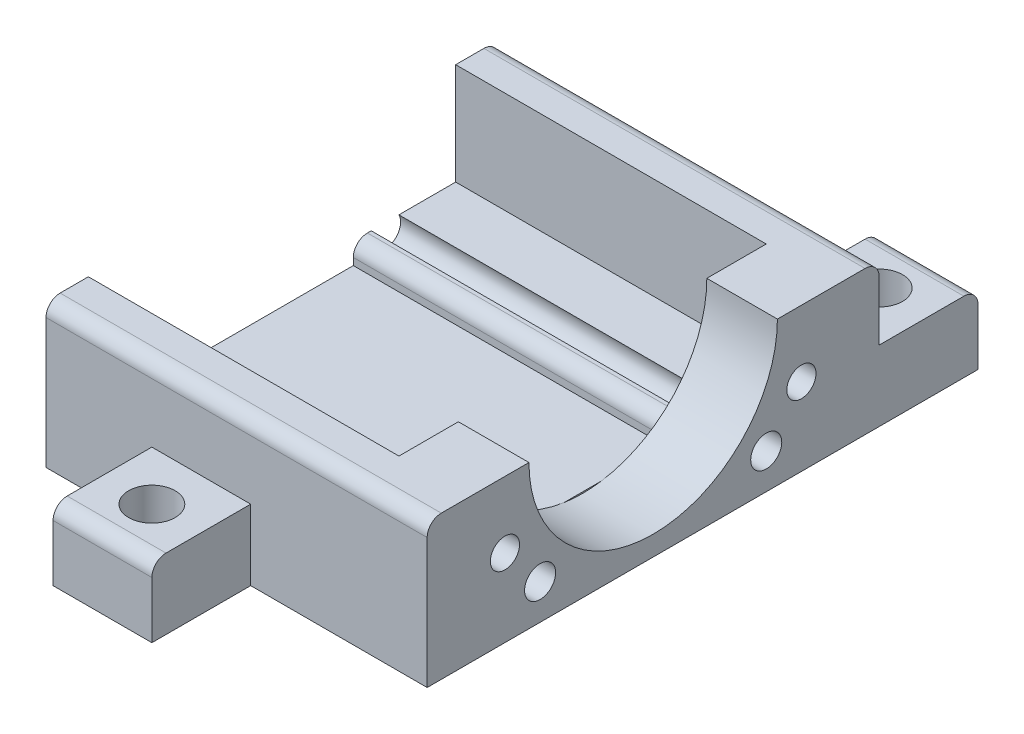
SolidWorks part; units mm, degrees
ref_plane "Front" through (0, 0, 0) normal (0, 0, 1) x (1, 0, 0)
ref_plane "Top" through (0, 0, 0) normal (0, 1, 0) x (1, 0, 0)
ref_plane "Right" through (0, 0, 0) normal (1, 0, 0) x (0, 0, -1)
sketch "Sketch1" plane through (0, 0, 0) normal (1, 0, 0) x (0, 0, -1)
  line L0 (-13.0089, 0) -> (13.0089, 0)
  line L1 (13.0089, 0) -> (13.0089, 3)
  line L2 (13.0089, 3) -> (5.7589, 3)
  line L3 (5.7589, 3) -> (5.7589, 1.5)
  line L4 (5.7589, 1.5) -> (-5.7589, 1.5)
  line L5 (-5.7589, 1.5) -> (-5.7589, 3)
  line L6 (-5.7589, 3) -> (-13.0089, 3)
  line L7 (-13.0089, 3) -> (-13.0089, 0)
  dimension "D1" = 3
  dimension "D2" = 7.25
  dimension "D3" = 26.0178
  dimension "D4" = 1.5
extrude "Boss-Extrude1" add sketch "Sketch1" along normal mid plane 22
sketch "Sketch3" plane through (0, 0, 0) normal (0, -1, 0) x (1, 0, 0)
  line L1 (-11, -13.0089) -> (11, -13.0089)
  line L2 (-11, -13.0089) -> (-11, -16.0089)
  line L3 (-11, -16.0089) -> (11, -16.0089)
  line L4 (11, -13.0089) -> (11, -16.0089)
  line L5 (-11, 13.0089) -> (11, 13.0089)
  line L6 (-11, 13.0089) -> (-11, 16.0089)
  line L7 (-11, 16.0089) -> (11, 16.0089)
  line L8 (11, 13.0089) -> (11, 16.0089)
  dimension "D1" = 3
  dimension "D2" = 22
  dimension "D3" = 3
  dimension "D4" = 22
extrude "Boss-Extrude2" add sketch "Sketch3" against normal blind 10.2
sketch "Sketch4" plane through (11, 0, 0) normal (1, 0, 0) x (0, 0, -1)
  line L0 (0, 0) -> (0, 10.2) construction
  line L1 (-16.0089, 0) -> (16.0089, 0) construction
  line L2 (-8.8, 10.2) -> (-16.0089, 10.2)
  line L3 (-16.0089, 10.2) -> (-16.0089, 0) construction
  line L4 (-16.0089, 10.2) -> (-16.0089, 0)
  line L5 (-16.0089, 0) -> (16.0089, 0)
  line L6 (16.0089, 0) -> (16.0089, 10.2)
  line L7 (16.0089, 10.2) -> (16.0089, 0) construction
  line L8 (16.0089, 10.2) -> (8.8, 10.2)
  arc A0 (-8.8, 10.2) -> (8.8, 10.2) centre (0, 10.2) ccw
  dimension "D1" = 8.8
  dimension "D2" = 10.2
extrude "Boss-Extrude3" add sketch "Sketch4" along normal blind 5
sketch "Sketch5" plane through (16, 0, 0) normal (1, 0, 0) x (0, 0, -1)
  line L0 (-16.0089, 5.5) -> (-10.5, 5.5) construction
  line L1 (-16.0089, 10.2) -> (-16.0089, 0) construction
  line L2 (-10.5, 5.5) -> (-10.5, 0) construction
  line L3 (-16.0089, 0) -> (16.0089, 0) construction
  line L4 (0, 0) -> (0, 10.2) construction
  line L5 (-16.0089, 2.5) -> (-8.0089, 2.5) construction
  line L6 (-8.0089, 2.5) -> (-8.0089, 0) construction
  circle A0 centre (-10.5, 5.5) radius 1.035
  circle A1 centre (10.5, 5.5) radius 1.035
  circle A2 centre (-8.0089, 2.5) radius 1.1
  circle A3 centre (8.0089, 2.5) radius 1.1
  dimension "D3" = 2.07
  dimension "D4" = 2.2
  dimension "D1" = 5.5089
  dimension "D2" = 5.5
  dimension "D5" = 8
  dimension "D6" = 2.5
extrude "Cut-Extrude1" cut sketch "Sketch5" against normal through all
sketch "Sketch6" plane through (0, 0, 0) normal (0, -1, 0) x (1, 0, 0)
  line L0 (16, 16.0089) -> (-11, 16.0089) construction
  line L1 (3.5, 16.0089) -> (-3.5, 16.0089)
  line L2 (3.5, 16.0089) -> (3.5, 23.0089)
  line L3 (3.5, 23.0089) -> (-3.5, 23.0089)
  line L4 (-3.5, 16.0089) -> (-3.5, 23.0089)
  line L5 (0, 0) -> (0, 16.0089) construction
  line L6 (16, -23.0089) -> (9, -23.0089)
  line L8 (16, -16.0089) -> (16, -23.0089)
  line L11 (9, -23.0089) -> (9, -16.0089)
  line L12 (9, -16.0089) -> (16, -16.0089)
  line L13 (-11, -16.0089) -> (16, -16.0089) construction
  dimension "D1" = 7
  dimension "D2" = 7
  dimension "D3" = 7
  dimension "D4" = 7
extrude "Boss-Extrude4" add sketch "Sketch6" against normal blind 5
sketch "Sketch7" plane through (0, 5, 0) normal (0, 1, 0) x (1, 0, 0)
  line L0 (0, -23.0089) -> (0, -19.5089) construction
  line L1 (3.5, -23.0089) -> (-3.5, -23.0089) construction
  line L2 (0, -19.5089) -> (3.5, -19.5089) construction
  line L3 (3.5, -16.0089) -> (3.5, -23.0089) construction
  line L4 (12.5, 23.0089) -> (12.5, 19.5089) construction
  line L5 (9, 23.0089) -> (16, 23.0089) construction
  line L6 (12.5, 19.5089) -> (16, 19.5089) construction
  line L7 (16, 23.0089) -> (16, 16.0089) construction
  circle A0 centre (0, -19.5089) radius 1.65
  circle A1 centre (12.5, 19.5089) radius 1.65
  dimension "D1" = 3.3
extrude "Cut-Extrude2" cut sketch "Sketch7" against normal through all
fillet "Fillet1" radius 1 6 edges at (12.5, 5, -23.0089) (2.5, 10.2, -16.0089) (2.5, 10.2, 16.0089) (0, 5, 23.0089) (0, 3, 5.7589) (0, 3, -5.7589)
